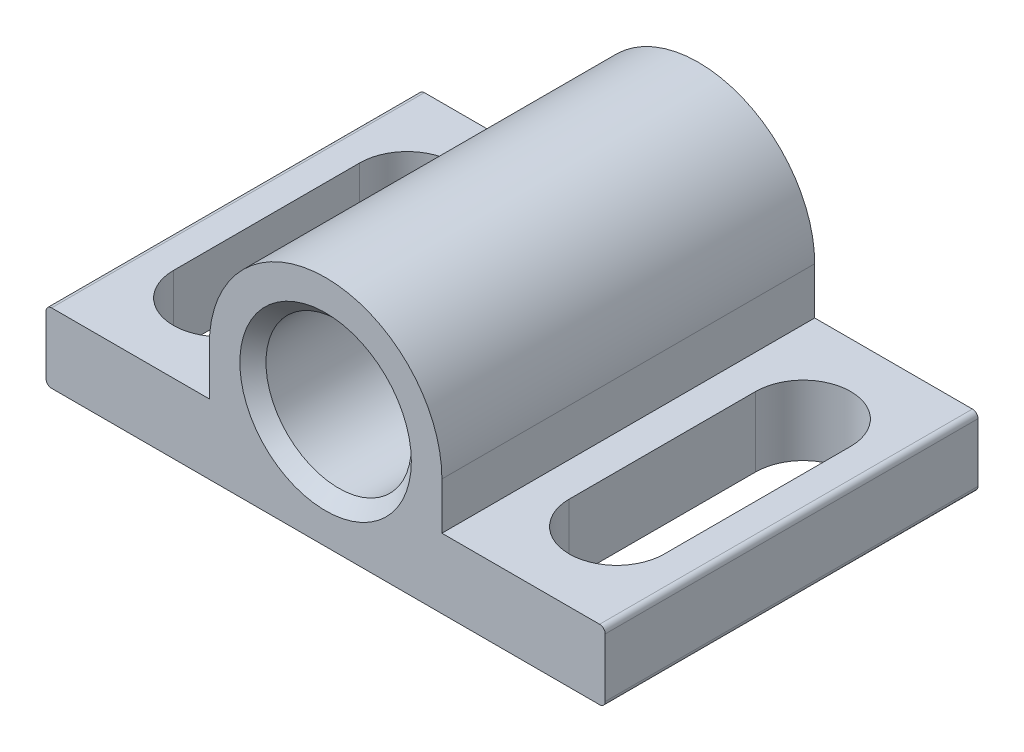
SolidWorks part; units mm, degrees
material "6105-T5"
ref_plane "Front Plane" through (0, 0, 0) normal (0, 0, 1) x (1, 0, 0)
ref_plane "Top Plane" through (0, 0, 0) normal (0, 1, 0) x (1, 0, 0)
ref_plane "Right Plane" through (0, 0, 0) normal (1, 0, 0) x (0, 0, -1)
sketch "Sketch1" plane through (0, 0, 0) normal (0, 0, 1) x (1, 0, 0)
  line L0 (0, 13.5001) -> (0, -2.3749) construction
  line L1 (-19.05, -2.3749) -> (19.05, -2.3749)
  line L2 (-19.05, -2.3749) -> (-19.05, 2.3749)
  line L3 (-19.05, 2.3749) -> (-7.9248, 2.3749)
  line L4 (19.05, -2.3749) -> (19.05, 2.3749)
  line L5 (-19.05, -2.3749) -> (19.05, 2.3749) construction
  line L6 (-19.05, 2.3749) -> (19.05, -2.3749) construction
  line L7 (-7.9248, 5.5753) -> (-7.9248, 2.3749)
  line L8 (7.9248, 5.5753) -> (7.9248, 2.3749)
  line L9 (7.9248, 2.3749) -> (19.05, 2.3749)
  arc A0 (7.9248, 5.5753) -> (-7.9248, 5.5753) centre (0, 5.5753) ccw
  circle A1 centre (0, 5.5753) radius 2.5527
  point P0 (0, 0)
  dimension "D3" = 15.8496
  dimension "D5" = 5.1054
  dimension "D1" = 4.7498
  dimension "D2" = 38.1
  dimension "D4" = 15.875
extrude "Boss-Extrude1" add sketch "Sketch1" along normal mid plane 25.4
fillet "Fillet1" radius 0.381 4 edges at (19.05, 2.3749, 0) (-19.05, -2.3749, 0) (-19.05, 2.3749, 0) (19.05, -2.3749, 0)
hole_wizard "1/2 (0.5) Diameter Hole2" positions "Sketch8" profile "Sketch7" hole size "1/2" standard "ANSI Inch"
sketch "Sketch8" plane through (0, 0, 12.7) normal (0, 0, 1) x (1, 0, 0)
  point P2 (0, 5.5753)
sketch "Sketch7" plane through (0, 5.5753, 12.7) normal (1, 0, 0) x (0, -1, 0)
  line L0 (0, 0) -> (0, 24.7478)
  line L1 (0, 24.7478) -> (4.953, 19.05)
  line L2 (4.953, 19.05) -> (4.953, 0)
  line L5 (4.953, 0) -> (0, 0)
  line L10 (0, 24.7478) -> (-4.953, 19.05) construction
  line L11 (0, -6.35) -> (0, 107.95) construction
  dimension "Hole Dia." = 9.906
  dimension "Hole Depth" = 19.05
  dimension "Drill Angle" = 82
chamfer "Chamfer2" distance 0.889 angle 45 1 edges at (4.953, 5.5753, 12.7)
sketch "Sketch9" plane through (0, 2.3749, 0) normal (0, 1, 0) x (1, 0, 0)
  line L0 (13.4874, 6.35) -> (13.4874, -6.35) construction
  line L1 (16.7259, 6.35) -> (16.7259, -6.35)
  line L2 (10.2489, 6.35) -> (10.2489, -6.35)
  line L3 (0, 0) -> (13.4874, 0) construction
  line L4 (0, 5.5659) -> (0, -3.7817) construction
  line L5 (-13.4874, 6.35) -> (-13.4874, -6.35) construction
  line L6 (-16.7259, 6.35) -> (-16.7259, -6.35)
  line L7 (-10.2489, 6.35) -> (-10.2489, -6.35)
  line L8 (19.05, 12.7) -> (19.05, -12.7) construction
  arc A0 (16.7259, 6.35) -> (10.2489, 6.35) centre (13.4874, 6.35) ccw
  arc A1 (10.2489, -6.35) -> (16.7259, -6.35) centre (13.4874, -6.35) ccw
  arc A2 (-16.7259, 6.35) -> (-10.2489, 6.35) centre (-13.4874, 6.35) cw
  arc A3 (-10.2489, -6.35) -> (-16.7259, -6.35) centre (-13.4874, -6.35) cw
  point P2 (13.4874, 0)
  point P14 (-13.4874, 0)
  dimension "D1" = 3.2385
  dimension "D2" = 12.7
  dimension "D3" = 5.5626
extrude "Cut-Extrude1" cut sketch "Sketch9" against normal blind 9.906
